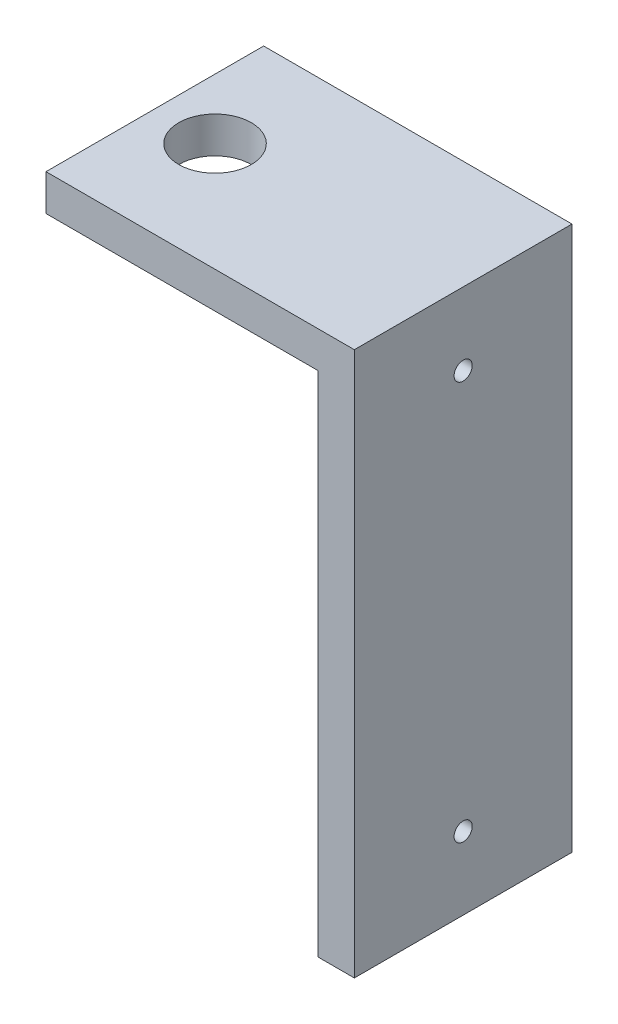
SolidWorks part; units mm, degrees
ref_plane "Front Plane" through (0, 0, 0) normal (0, 0, 1) x (1, 0, 0)
ref_plane "Top Plane" through (0, 0, 0) normal (0, 1, 0) x (1, 0, 0)
ref_plane "Right Plane" through (0, 0, 0) normal (1, 0, 0) x (0, 0, -1)
sketch "Sketch1" plane through (0, 0, 0) normal (0, 0, 1) x (1, 0, 0)
  line L0 (8.634, 8.4694) -> (23.634, 8.4694)
  line L1 (23.634, 8.4694) -> (23.634, -19.5306)
  line L2 (23.634, -19.5306) -> (25.634, -19.5306)
  line L3 (25.634, -19.5306) -> (25.634, 10.4694)
  line L4 (25.634, 10.4694) -> (8.634, 10.4694)
  line L5 (8.634, 10.4694) -> (8.634, 8.4694)
  line L6 (21.634, 5.4694) -> (21.634, -19.5306) construction
  dimension "D1" = 2
  dimension "D2" = 2
  dimension "D3" = 15
  dimension "D4" = 30
  dimension "D5" = 2
extrude "Boss-Extrude1" add sketch "Sketch1" along normal mid plane 12
sketch "Sketch2" plane through (0, 10.4694, 0) normal (0, 1, 0) x (1, 0, 0)
  line L0 (8.634, -6) -> (8.634, 6) construction
  line L1 (8.634, 0) -> (25.634, 0) construction
  line L2 (25.634, -6) -> (25.634, 6) construction
  circle A0 centre (11.9532, 0) radius 2
  dimension "D1" = 4
extrude "Cut-Extrude1" cut sketch "Sketch2" against normal blind 10
sketch "Sketch3" plane through (25.634, 0, 0) normal (1, 0, 0) x (0, 0, -1)
  line L0 (0, 10.4694) -> (0, -19.5306) construction
  line L1 (-6, 10.4694) -> (6, 10.4694) construction
  line L2 (-6, -19.5306) -> (6, -19.5306) construction
  circle A0 centre (0, -15.5306) radius 0.5
  circle A1 centre (0, 6.4694) radius 0.5
  dimension "D1" = 1
  dimension "D4" = 1
  dimension "D2" = 4
  dimension "D3" = 4
  dimension "D5" = 22
extrude "Cut-Extrude2" cut sketch "Sketch3" against normal up to next
